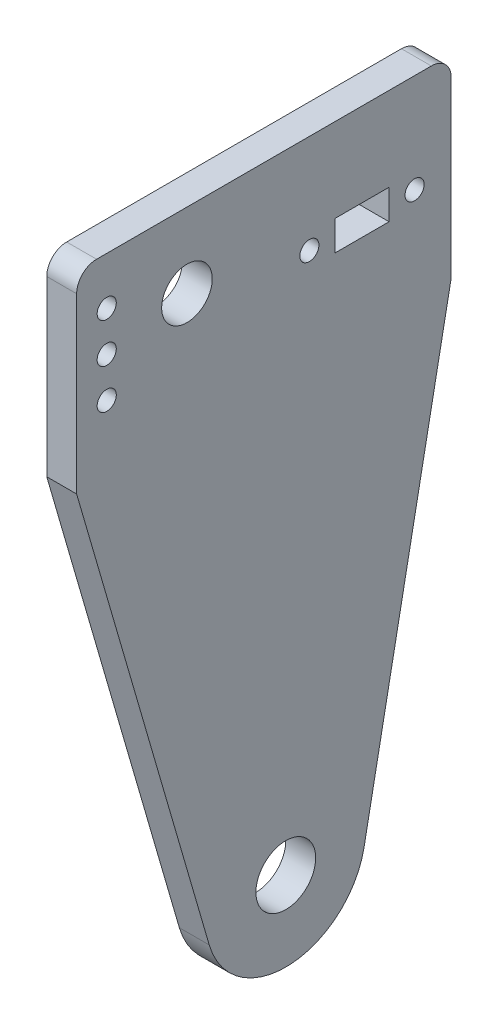
SolidWorks part; units mm, degrees
ref_plane "Front Plane" through (0, 0, 0) normal (0, 0, 1) x (1, 0, 0)
ref_plane "Top Plane" through (0, 0, 0) normal (0, 1, 0) x (1, 0, 0)
ref_plane "Right Plane" through (0, 0, 0) normal (1, 0, 0) x (0, 0, -1)
sketch "Sketch1" plane through (0, 0, 0) normal (1, 0, 0) x (0, 0, -1)
  line L0 (42.1132, 8.7376) -> (42.1132, -18.8943)
  line L1 (-17.5768, 8.7376) -> (-17.5768, -18.8943)
  line L2 (38.9382, 11.9126) -> (-14.4018, 11.9126)
  line L3 (-15.7317, -3.8354) -> (28.7183, -3.8354) construction
  line L4 (-17.5768, -18.8943) -> (3.5512, -91.6902)
  line L5 (42.1132, -18.8943) -> (28.2157, -90.5678)
  line L7 (23.5712, -6.2167) -> (32.2072, -6.2167)
  line L8 (23.5712, -6.2167) -> (23.5712, -1.4542)
  line L10 (-12.8842, 9.4615) -> (-9.4806, 9.4615) construction
  line L11 (23.5712, -1.4542) -> (32.2072, -1.4542)
  line L12 (32.2072, -6.2167) -> (32.2072, -1.4542)
  line L13 (23.5712, -6.2167) -> (32.2072, -1.4542) construction
  line L14 (23.5712, -1.4542) -> (32.2072, -6.2167) construction
  circle A0 centre (15.7479, -88.1503) radius 4.7625
  arc A1 (3.5512, -91.6902) -> (28.2157, -90.5678) centre (15.7479, -88.1503) ccw
  circle A2 centre (0, 0) radius 4.0323
  circle A3 centre (-12.7825, 4.3307) radius 1.524
  arc A4 (42.1132, 8.7376) -> (38.9382, 11.9126) centre (38.9382, 8.7376) ccw
  circle A5 centre (15.7479, -88.1503) radius 77.47 construction
  circle A6 centre (36.2712, -3.8354) radius 1.524
  circle A7 centre (-12.7825, -2.0193) radius 1.524
  circle A8 centre (-12.7825, -8.3693) radius 1.524
  arc A10 (-17.5768, 8.7376) -> (-14.4018, 11.9126) centre (-14.4018, 8.7376) cw
  circle A11 centre (19.5072, -3.8354) radius 1.524
  point P21 (27.8892, -3.8354)
  point P39 (105.0691, -38.1835)
  dimension "D1" = 3.175
  dimension "D3" = 154.94
  dimension "D4" = 8.0645
  dimension "D6" = 3.048
  dimension "D9" = 3.048
  dimension "D13" = 5.1308
  dimension "D5" = 11.9126
  dimension "D8" = 5.842
  dimension "D10" = 54.8957
  dimension "D11" = 15.748
  dimension "D12" = 6.35
  dimension "D14" = 59.69
  dimension "D16" = 4.7625
  dimension "D17" = 8.382
  dimension "D18" = 8.636
  dimension "D19" = 42.1132
  dimension "D20" = 6.35
extrude "Boss-Extrude1" add sketch "Sketch1" along normal blind 4.7625
